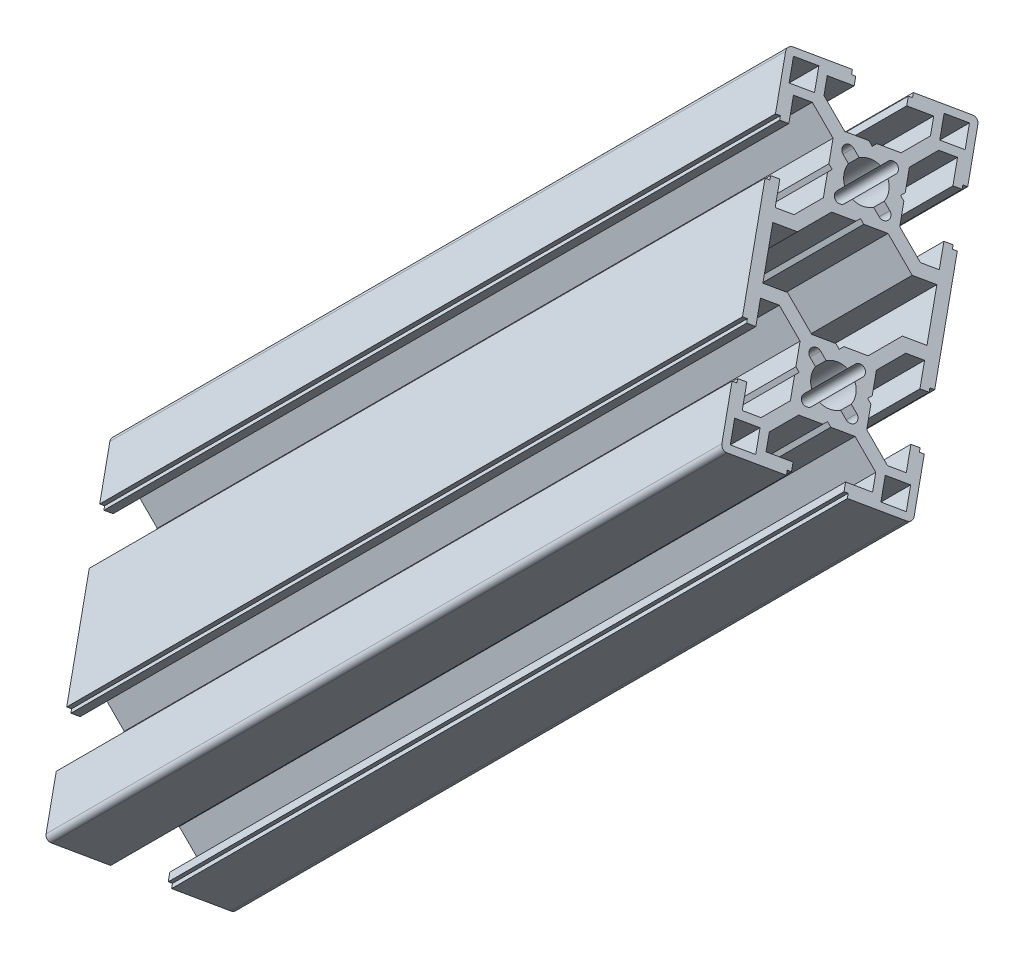
SolidWorks part; units mm, degrees
material "6061 Alloy"
ref_plane "Front Plane" through (0, 0, 0) normal (0, 0, 1) x (1, 0, 0)
ref_plane "Top Plane" through (0, 0, 0) normal (0, 1, 0) x (1, 0, 0)
ref_plane "Right Plane" through (0, 0, 0) normal (1, 0, 0) x (0, 0, -1)
sketch3d "3DSketch1"
  line L0 (0, 0, 0) -> (-127.2792, -127.2792, 0)
  dimension "D1" = 180
other "T-slot CNCCAT-3060(1)"
ref_plane "Plane1" through (0, 0, 0) normal (-0.7071, -0.7071, 0) x (0.5, -0.5, 0.7071)
sketch "Sketch2" plane through (0, 0, 0) normal (-0.7071, -0.7071, 0) x (0.5, -0.5, 0.7071)
  line L0 (-15, 0) -> (15, 0) construction
  line L1 (30, 15) -> (-30, 15) construction
  line L2 (30, 15) -> (30, -15) construction
  line L3 (24.7696, 13.7304) -> (24.7696, 9.7696)
  line L4 (28.7304, 13.7304) -> (24.7696, 13.7304)
  line L5 (28.7304, 9.7696) -> (28.7304, 13.7304)
  line L6 (24.7696, 9.7696) -> (28.7304, 9.7696)
  line L7 (19.1095, -2.6952) -> (18.0788, -1.6646)
  line L8 (16.6646, -3.0788) -> (17.6952, -4.1095)
  line L9 (-4.492, -12.8) -> (4.492, -12.8)
  line L10 (-4.492, -8.9524) -> (-4.492, -12.8)
  line L11 (-9.0433, -4.4011) -> (-4.492, -8.9524)
  line L12 (-9.0433, -0.6196) -> (-9.0433, -4.4011)
  line L13 (-9.6629, 0) -> (-9.0433, -0.6196)
  line L14 (-9.0433, 0.6196) -> (-9.6629, 0)
  line L15 (-9.0433, 4.4011) -> (-9.0433, 0.6196)
  line L16 (-4.492, 8.9524) -> (-9.0433, 4.4011)
  line L17 (-4.492, 12.8) -> (-4.492, 8.9524)
  line L18 (4.492, 12.8) -> (-4.492, 12.8)
  line L19 (4.492, 8.9524) -> (4.492, 12.8)
  line L20 (9.0433, 4.4011) -> (4.492, 8.9524)
  line L21 (9.0433, 0.6196) -> (9.0433, 4.4011)
  line L22 (9.6629, 0) -> (9.0433, 0.6196)
  line L23 (9.0433, -0.6196) -> (9.6629, 0)
  line L24 (9.0433, -4.4011) -> (9.0433, -0.6196)
  line L25 (4.492, -8.9524) -> (9.0433, -4.4011)
  line L26 (4.492, -12.8) -> (4.492, -8.9524)
  line L27 (12.3048, -4.1095) -> (13.3354, -3.0788)
  line L28 (11.9212, -1.6646) -> (10.8905, -2.6952)
  line L29 (10.8905, 2.6952) -> (11.9212, 1.6646)
  line L30 (13.3354, 3.0788) -> (12.3048, 4.1095)
  line L31 (17.6952, 4.1095) -> (16.6646, 3.0788)
  line L32 (18.0788, 1.6646) -> (19.1095, 2.6952)
  line L33 (28.7304, -13.7304) -> (28.7304, -9.7696)
  line L34 (24.7696, -13.7304) -> (28.7304, -13.7304)
  line L35 (24.7696, -9.7696) -> (24.7696, -13.7304)
  line L36 (28.7304, -9.7696) -> (24.7696, -9.7696)
  line L37 (-28.7304, 13.7304) -> (-28.7304, 9.7696)
  line L38 (-24.7696, 13.7304) -> (-28.7304, 13.7304)
  line L39 (-24.7696, 9.7696) -> (-24.7696, 13.7304)
  line L40 (-28.7304, 9.7696) -> (-24.7696, 9.7696)
  line L41 (-19.1095, 2.6952) -> (-18.0788, 1.6646)
  line L42 (-16.6646, 3.0788) -> (-17.6952, 4.1095)
  line L43 (-12.3048, 4.1095) -> (-13.3354, 3.0788)
  line L44 (-11.9212, 1.6646) -> (-10.8905, 2.6952)
  line L45 (-10.8905, -2.6952) -> (-11.9212, -1.6646)
  line L46 (-13.3354, -3.0788) -> (-12.3048, -4.1095)
  line L47 (-17.6952, -4.1095) -> (-16.6646, -3.0788)
  line L48 (-18.0788, -1.6646) -> (-19.1095, -2.6952)
  line L49 (-24.7696, -13.7304) -> (-24.7696, -9.7696)
  line L50 (-28.7304, -13.7304) -> (-24.7696, -13.7304)
  line L51 (-28.7304, -9.7696) -> (-28.7304, -13.7304)
  line L52 (-24.7696, -9.7696) -> (-28.7304, -9.7696)
  line L53 (30, -15) -> (-30, -15) construction
  line L54 (-30, 15) -> (-30, -15) construction
  line L55 (30, 15) -> (-30, -15) construction
  line L56 (30, -15) -> (-30, 15) construction
  line L57 (-20.3371, 0) -> (-20.9567, -0.6196)
  line L58 (-20.9567, -0.6196) -> (-20.9567, -4.4011)
  line L59 (-20.9567, -4.4011) -> (-24.8637, -8.308)
  line L60 (-24.8637, -8.308) -> (-27.8, -8.308)
  line L61 (-27.8, -8.308) -> (-27.8, -4.1)
  line L62 (-27.8, -4.1) -> (-29.2339, -4.1)
  line L63 (-29.2339, -4.1) -> (-29.2339, -4.7563)
  line L64 (-29.2339, -4.7563) -> (-30, -4.7563)
  line L65 (-30, -4.7563) -> (-30, -14)
  line L66 (-29, -15) -> (-19.7563, -15)
  line L67 (-19.7563, -15) -> (-19.7563, -14.2339)
  line L68 (-19.7563, -14.2339) -> (-19.1, -14.2339)
  line L69 (-19.1, -14.2339) -> (-19.1, -12.8)
  line L70 (-19.1, -12.8) -> (-23.308, -12.8)
  line L71 (-23.308, -12.8) -> (-23.308, -9.8637)
  line L72 (-23.308, -9.8637) -> (-19.4011, -5.9567)
  line L73 (-19.4011, -5.9567) -> (-15.6196, -5.9567)
  line L74 (-15.6196, -5.9567) -> (-15, -5.3371)
  line L75 (-15, -5.3371) -> (-14.3804, -5.9567)
  line L76 (-14.3804, -5.9567) -> (-10.5989, -5.9567)
  line L77 (-10.5989, -5.9567) -> (-6.692, -9.8637)
  line L78 (-6.692, -9.8637) -> (-6.692, -12.8)
  line L79 (-6.692, -12.8) -> (-10.9, -12.8)
  line L80 (-10.9, -12.8) -> (-10.9, -14.2339)
  line L81 (-10.9, -14.2339) -> (-10.2437, -14.2339)
  line L82 (-10.2437, -14.2339) -> (-10.2437, -15)
  line L83 (-10.2437, -15) -> (10.2437, -15)
  line L84 (10.2437, -15) -> (10.2437, -14.2339)
  line L85 (10.2437, -14.2339) -> (10.9, -14.2339)
  line L86 (10.9, -14.2339) -> (10.9, -12.8)
  line L87 (10.9, -12.8) -> (6.692, -12.8)
  line L88 (6.692, -12.8) -> (6.692, -9.8637)
  line L89 (6.692, -9.8637) -> (10.5989, -5.9567)
  line L90 (10.5989, -5.9567) -> (14.3804, -5.9567)
  line L91 (14.3804, -5.9567) -> (15, -5.3371)
  line L92 (15, -5.3371) -> (15.6196, -5.9567)
  line L93 (15.6196, -5.9567) -> (19.4011, -5.9567)
  line L94 (19.4011, -5.9567) -> (23.308, -9.8637)
  line L95 (23.308, -9.8637) -> (23.308, -12.8)
  line L96 (23.308, -12.8) -> (19.1, -12.8)
  line L97 (19.1, -12.8) -> (19.1, -14.2339)
  line L98 (19.1, -14.2339) -> (19.7563, -14.2339)
  line L99 (19.7563, -14.2339) -> (19.7563, -15)
  line L100 (19.7563, -15) -> (29, -15)
  line L101 (30, -14) -> (30, -4.7563)
  line L102 (30, -4.7563) -> (29.2339, -4.7563)
  line L103 (29.2339, -4.7563) -> (29.2339, -4.1)
  line L104 (29.2339, -4.1) -> (27.8, -4.1)
  line L105 (27.8, -4.1) -> (27.8, -8.308)
  line L106 (27.8, -8.308) -> (24.8637, -8.308)
  line L107 (24.8637, -8.308) -> (20.9567, -4.4011)
  line L108 (20.9567, -4.4011) -> (20.9567, -0.6196)
  line L109 (20.9567, -0.6196) -> (20.3371, 0)
  line L110 (20.3371, 0) -> (20.9567, 0.6196)
  line L111 (20.9567, 0.6196) -> (20.9567, 4.4011)
  line L112 (20.9567, 4.4011) -> (24.8637, 8.308)
  line L113 (24.8637, 8.308) -> (27.8, 8.308)
  line L114 (27.8, 8.308) -> (27.8, 4.1)
  line L115 (27.8, 4.1) -> (29.2339, 4.1)
  line L116 (29.2339, 4.1) -> (29.2339, 4.7563)
  line L117 (29.2339, 4.7563) -> (30, 4.7563)
  line L118 (30, 4.7563) -> (30, 14)
  line L119 (29, 15) -> (19.7563, 15)
  line L120 (19.7563, 15) -> (19.7563, 14.2339)
  line L121 (19.7563, 14.2339) -> (19.1, 14.2339)
  line L122 (19.1, 14.2339) -> (19.1, 12.8)
  line L123 (19.1, 12.8) -> (23.308, 12.8)
  line L124 (23.308, 12.8) -> (23.308, 9.8637)
  line L125 (23.308, 9.8637) -> (19.4011, 5.9567)
  line L126 (19.4011, 5.9567) -> (15.6196, 5.9567)
  line L127 (15.6196, 5.9567) -> (15, 5.3371)
  line L128 (15, 5.3371) -> (14.3804, 5.9567)
  line L129 (14.3804, 5.9567) -> (10.5989, 5.9567)
  line L130 (10.5989, 5.9567) -> (6.692, 9.8637)
  line L131 (6.692, 9.8637) -> (6.692, 12.8)
  line L132 (6.692, 12.8) -> (10.9, 12.8)
  line L133 (10.9, 12.8) -> (10.9, 14.2339)
  line L134 (10.9, 14.2339) -> (10.2437, 14.2339)
  line L135 (10.2437, 14.2339) -> (10.2437, 15)
  line L136 (10.2437, 15) -> (-10.2437, 15)
  line L137 (-10.2437, 15) -> (-10.2437, 14.2339)
  line L138 (-10.2437, 14.2339) -> (-10.9, 14.2339)
  line L139 (-10.9, 14.2339) -> (-10.9, 12.8)
  line L140 (-10.9, 12.8) -> (-6.692, 12.8)
  line L141 (-6.692, 12.8) -> (-6.692, 9.8637)
  line L142 (-6.692, 9.8637) -> (-10.5989, 5.9567)
  line L143 (-10.5989, 5.9567) -> (-14.3804, 5.9567)
  line L144 (-14.3804, 5.9567) -> (-15, 5.3371)
  line L145 (-15, 5.3371) -> (-15.6196, 5.9567)
  line L146 (-15.6196, 5.9567) -> (-19.4011, 5.9567)
  line L147 (-19.4011, 5.9567) -> (-23.308, 9.8637)
  line L148 (-23.308, 9.8637) -> (-23.308, 12.8)
  line L149 (-23.308, 12.8) -> (-19.1, 12.8)
  line L150 (-19.1, 12.8) -> (-19.1, 14.2339)
  line L151 (-19.1, 14.2339) -> (-19.7563, 14.2339)
  line L152 (-19.7563, 14.2339) -> (-19.7563, 15)
  line L153 (-19.7563, 15) -> (-29, 15)
  line L154 (-30, 14) -> (-30, 4.7563)
  line L155 (-30, 4.7563) -> (-29.2339, 4.7563)
  line L156 (-29.2339, 4.7563) -> (-29.2339, 4.1)
  line L157 (-29.2339, 4.1) -> (-27.8, 4.1)
  line L158 (-27.8, 4.1) -> (-27.8, 8.308)
  line L159 (-27.8, 8.308) -> (-24.8637, 8.308)
  line L160 (-24.8637, 8.308) -> (-20.9567, 4.4011)
  line L161 (-20.9567, 4.4011) -> (-20.9567, 0.6196)
  line L162 (-20.9567, 0.6196) -> (-20.3371, 0)
  arc A0 (17.6952, -4.1095) -> (19.1095, -2.6952) centre (18.4023, -3.4023) ccw
  arc A1 (13.3354, -3.0788) -> (16.6646, -3.0788) centre (15, 0) ccw
  arc A2 (10.8905, -2.6952) -> (12.3048, -4.1095) centre (11.5977, -3.4023) ccw
  arc A3 (11.9212, 1.6646) -> (11.9212, -1.6646) centre (15, 0) ccw
  arc A4 (12.3048, 4.1095) -> (10.8905, 2.6952) centre (11.5977, 3.4023) ccw
  arc A5 (16.6646, 3.0788) -> (13.3354, 3.0788) centre (15, 0) ccw
  arc A6 (19.1095, 2.6952) -> (17.6952, 4.1095) centre (18.4023, 3.4023) ccw
  arc A7 (18.0788, -1.6646) -> (18.0788, 1.6646) centre (15, 0) ccw
  arc A8 (-17.6952, 4.1095) -> (-19.1095, 2.6952) centre (-18.4023, 3.4023) ccw
  arc A9 (-13.3354, 3.0788) -> (-16.6646, 3.0788) centre (-15, 0) ccw
  arc A10 (-10.8905, 2.6952) -> (-12.3048, 4.1095) centre (-11.5977, 3.4023) ccw
  arc A11 (-11.9212, -1.6646) -> (-11.9212, 1.6646) centre (-15, 0) ccw
  arc A12 (-12.3048, -4.1095) -> (-10.8905, -2.6952) centre (-11.5977, -3.4023) ccw
  arc A13 (-16.6646, -3.0788) -> (-13.3354, -3.0788) centre (-15, 0) ccw
  arc A14 (-19.1095, -2.6952) -> (-17.6952, -4.1095) centre (-18.4023, -3.4023) ccw
  arc A15 (-18.0788, 1.6646) -> (-18.0788, -1.6646) centre (-15, 0) ccw
  arc A16 (-30, -14) -> (-29, -15) centre (-29, -14) ccw
  arc A17 (29, -15) -> (30, -14) centre (29, -14) ccw
  arc A18 (30, 14) -> (29, 15) centre (29, 14) ccw
  arc A19 (-29, 15) -> (-30, 14) centre (-29, 14) ccw
  point P92 (0, 0)
  point P94 (0, 0)
  point P103 (0, 15)
  point P105 (-30, -15)
  point P107 (-30, 15)
  point P109 (0, -15)
  point P111 (30, 0)
  point P113 (30, -15)
  point P115 (30, 15)
  point P117 (-30, 0)
  point P210 (0, 0)
